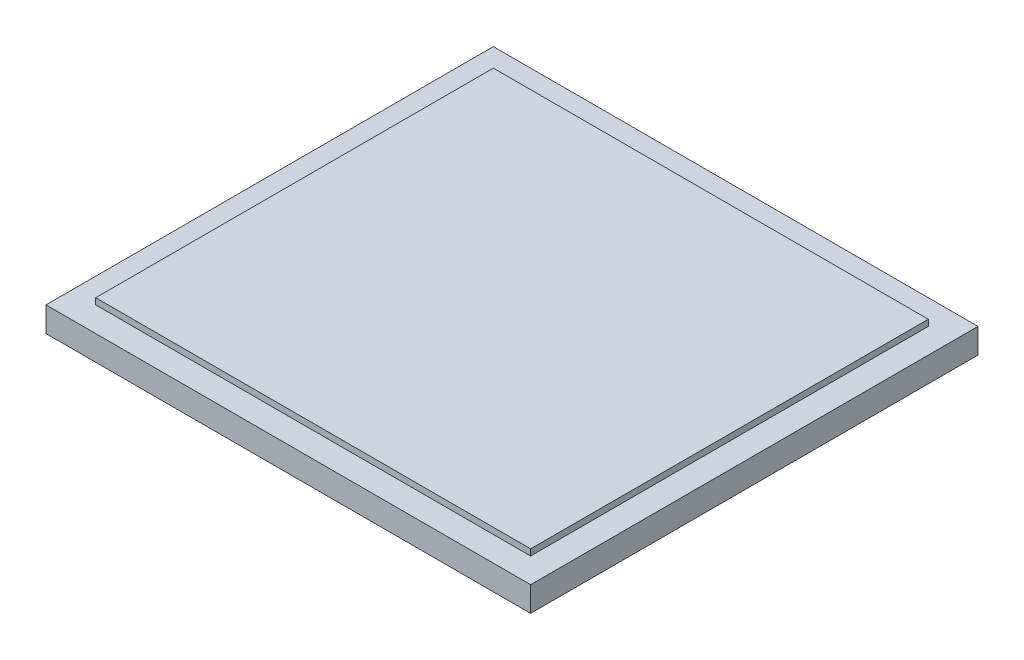
SolidWorks part; units mm, degrees
ref_plane "Front Plane" through (0, 0, 0) normal (0, 0, 1) x (1, 0, 0)
ref_plane "Top Plane" through (0, 0, 0) normal (0, 1, 0) x (1, 0, 0)
ref_plane "Right Plane" through (0, 0, 0) normal (1, 0, 0) x (0, 0, -1)
sketch "Sketch2" plane through (0, 0, 0) normal (0, 1, 0) x (1, 0, 0)
  line L1 (0, 0) -> (195, 0)
  line L2 (0, 0) -> (0, 180)
  line L3 (0, 180) -> (195, 180)
  line L4 (195, 0) -> (195, 180)
  dimension "D1" = 195
  dimension "D2" = 180
extrude "Boss-Extrude1" add sketch "Sketch2" along normal blind 10
sketch "Sketch3" plane through (0, 10, 0) normal (0, 1, 0) x (1, 0, 0)
  line L8 (10, 170) -> (10, 10)
  line L9 (10, 10) -> (185, 10)
  line L10 (185, 10) -> (185, 170)
  line L11 (185, 170) -> (10, 170)
  line L12 (10, 170) -> (10, 10)
  line L13 (10, 10) -> (185, 10)
  line L14 (185, 10) -> (185, 170)
  line L15 (185, 170) -> (10, 170)
  dimension "D1" = 10
extrude "Boss-Extrude2" add sketch "Sketch3" along normal blind 2.5
